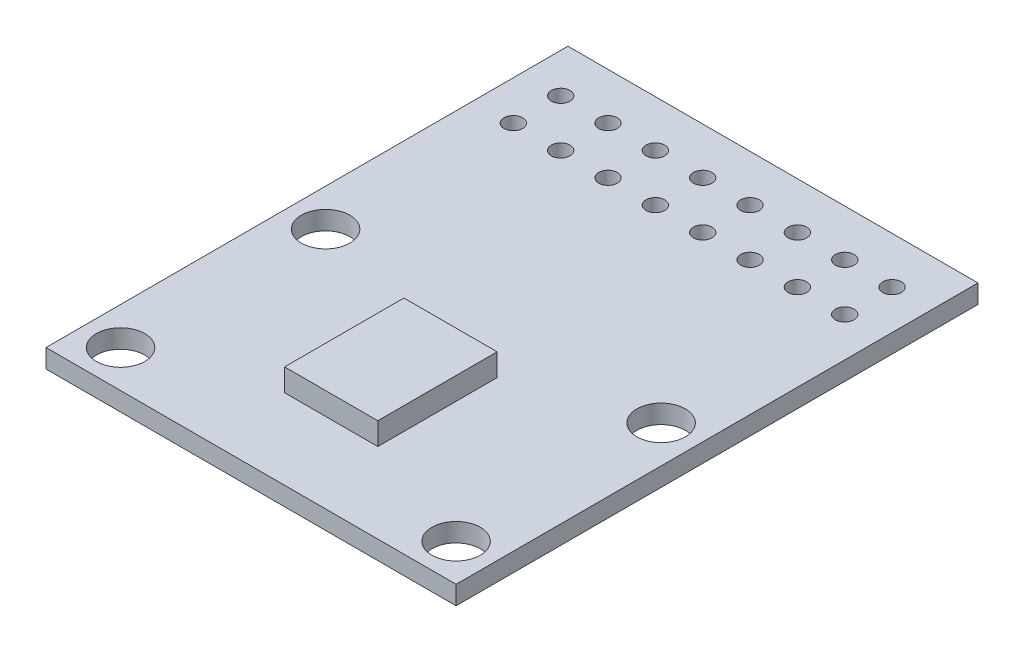
SolidWorks part; units mm, degrees
ref_plane "Front" through (0, 0, 0) normal (0, 0, 1) x (1, 0, 0)
ref_plane "Top" through (0, 0, 0) normal (0, 1, 0) x (1, 0, 0)
ref_plane "Right" through (0, 0, 0) normal (1, 0, 0) x (0, 0, -1)
sketch "Sketch1" plane through (0, 0, 0) normal (0, 1, 0) x (1, 0, 0)
  line L7 (11, 20.5) -> (-11, 20.5)
  line L8 (11, 20.5) -> (11, -7.5)
  line L9 (11, -7.5) -> (-11, -7.5)
  line L10 (-11, 20.5) -> (-11, -7.5)
extrude "Boss-Extrude1" add sketch "Sketch1" along normal blind 1
sketch "Sketch2" plane through (0, 1, 0) normal (0, 1, 0) x (1, 0, 0)
  circle A0 centre (-9, -5.5) radius 1.3
  circle A1 centre (9, -5.5) radius 1.3
  circle A2 centre (9, 5.5) radius 1.3
  circle A3 centre (-9, 5.5) radius 1.3
  dimension "D1" = 2
  dimension "D2" = 2
extrude "Cut-Extrude8" cut sketch "Sketch2" against normal through all
sketch "Sketch3" plane through (0, 1, 0) normal (0, 1, 0) x (1, 0, 0)
  line L5 (-2.5, 3.2) -> (2.5, 3.2)
  line L6 (-2.5, 3.2) -> (-2.5, -3.2)
  line L7 (-2.5, -3.2) -> (2.5, -3.2)
  line L8 (2.5, 3.2) -> (2.5, -3.2)
  line L9 (-2.5, 3.2) -> (2.5, -3.2) construction
  line L10 (-2.5, -3.2) -> (2.5, 3.2) construction
  point P4 (0, 0)
extrude "IC" add sketch "Sketch3" along normal blind 1.2
sketch "Sketch4" plane through (0, 2.2, 0) normal (0, 1, 0) x (1, 0, 0)
  circle A0 centre (-8.89, 15.46) radius 0.5
  circle A1 centre (-6.35, 15.46) radius 0.5
  circle A2 centre (-3.81, 15.46) radius 0.5
  circle A3 centre (-1.27, 15.46) radius 0.5
  circle A4 centre (1.27, 15.46) radius 0.5
  circle A5 centre (3.81, 15.46) radius 0.5
  circle A6 centre (6.35, 15.46) radius 0.5
  circle A7 centre (8.89, 15.46) radius 0.5
  circle A8 centre (-6.35, 18) radius 0.5
  circle A9 centre (-3.81, 18) radius 0.5
  circle A10 centre (-1.27, 18) radius 0.5
  circle A11 centre (1.27, 18) radius 0.5
  circle A12 centre (3.81, 18) radius 0.5
  circle A13 centre (6.35, 18) radius 0.5
  circle A14 centre (8.89, 18) radius 0.5
  circle A15 centre (-8.89, 18) radius 0.5
  dimension "D1" = 8
  dimension "D2" = 2
extrude "Cut-Extrude9" cut sketch "Sketch4" against normal through all
